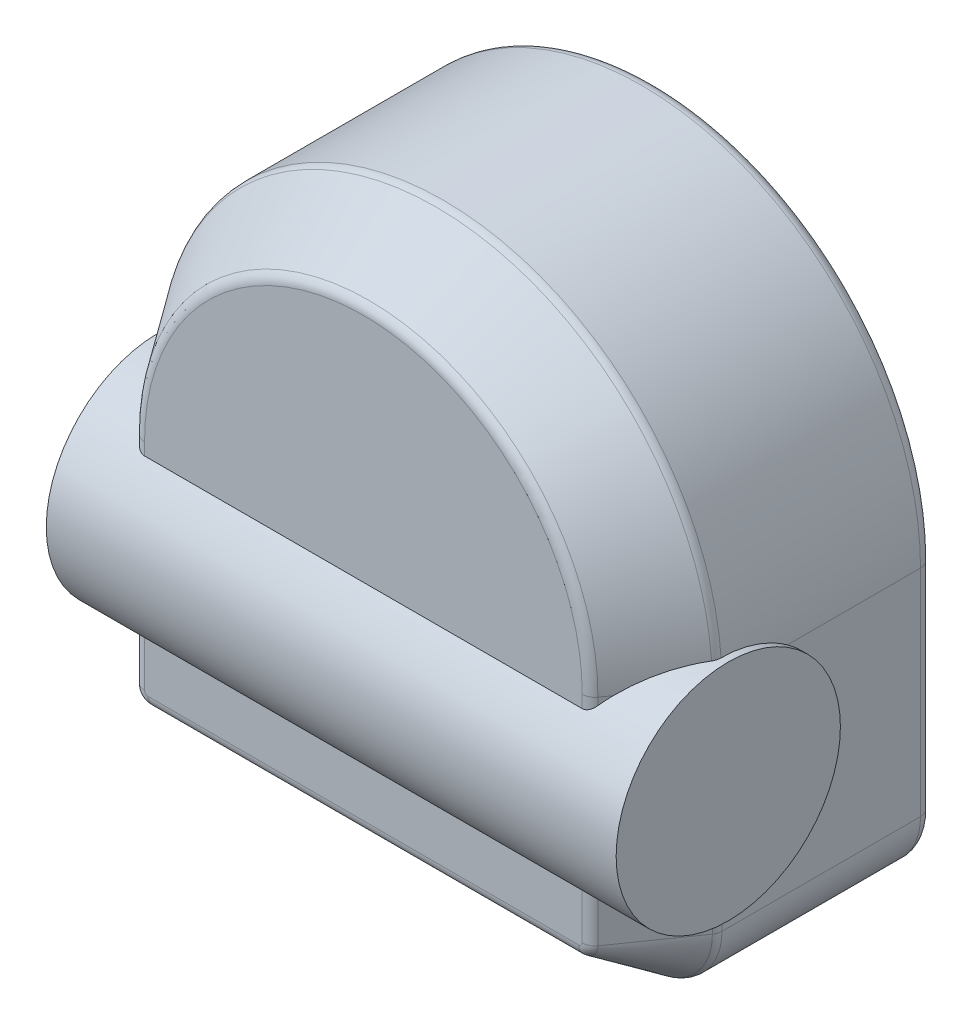
SolidWorks part; units mm, degrees
ref_plane "Front Plane" through (0, 0, 0) normal (0, 0, 1) x (1, 0, 0)
ref_plane "Top Plane" through (0, 0, 0) normal (0, 1, 0) x (1, 0, 0)
ref_plane "Right Plane" through (0, 0, 0) normal (1, 0, 0) x (0, 0, -1)
sketch "Sketch1" plane through (0, 0, 0) normal (0, 0, 1) x (1, 0, 0)
  line L1 (220.06, 110.03) -> (-220.06, 110.03)
  line L2 (220.06, 110.03) -> (220.06, -60.03)
  line L3 (170.06, -110.03) -> (-170.06, -110.03)
  line L4 (-220.06, 110.03) -> (-220.06, -60.03)
  line L5 (220.06, 110.03) -> (-220.06, -110.03) construction
  line L6 (220.06, -110.03) -> (-220.06, 110.03) construction
  arc A0 (-220.06, 110.03) -> (220.06, 110.03) centre (0, 110.03) cw
  arc A1 (220.06, -60.03) -> (170.06, -110.03) centre (170.06, -60.03) cw
  arc A2 (-170.06, -110.03) -> (-220.06, -60.03) centre (-170.06, -60.03) cw
  point P0 (0, 0)
  dimension "D3" = 50
  dimension "D1" = 440.12
  dimension "D2" = 220.06
extrude "Boss-Extrude1" add sketch "Sketch1" along normal mid plane 230 contours A0 L1 | A2 L3 A1 L2 L1 L4
chamfer "Chamfer3" distance 60 angle 35 6 edges at (220.06, 25, 115) (205.4153, -95.3853, 115) (0, -110.03, 115) (-205.4153, -95.3853, 115) (-220.06, 25, 115) (0, 330.09, 115)
fillet "Fillet1" radius 10 18 edges at (-220.06, 25, 55) (-205.4153, -95.3853, 55) (0, -110.03, 55) (205.4153, -95.3853, 55) (220.06, 25, 55) (0, -68.0175, 115) (-175.708, -65.678, 115) (-178.0475, 25, 115) (0, 288.0775, 115) (178.0475, 25, 115) (175.708, -65.678, 115) (0, 330.09, 55) (-220.06, 25, -115) (-205.4153, -95.3853, -115) (0, -110.03, -115) (205.4153, -95.3853, -115) (220.06, 25, -115) (0, 330.09, -115)
sketch "Sketch2" plane through (0, 0, 0) normal (1, 0, 0) x (0, 0, -1)
  line L0 (-51.847, 110.03) -> (105, 110.03) construction
  line L1 (-51.847, -60.03) -> (-51.847, 110.03) construction
  circle A0 centre (-51.847, 38.15) radius 88.57
  dimension "D1" = 177.14
  dimension "D2" = 71.88
extrude "Boss-Extrude2" add sketch "Sketch2" along normal mid plane 450.12
sketch "Sketch3" plane through (0, 0, -115) normal (0, 0, -1) x (-1, 0, 0)
  line L0 (170.06, -110.03) -> (-170.06, -110.03) construction
  circle A0 centre (0, 110.03) radius 50
  point P4 (0, 0)
  dimension "D1" = 100
  dimension "D2" = 220.06
extrude "Cut-Extrude1" cut sketch "Sketch3" against normal blind 100
